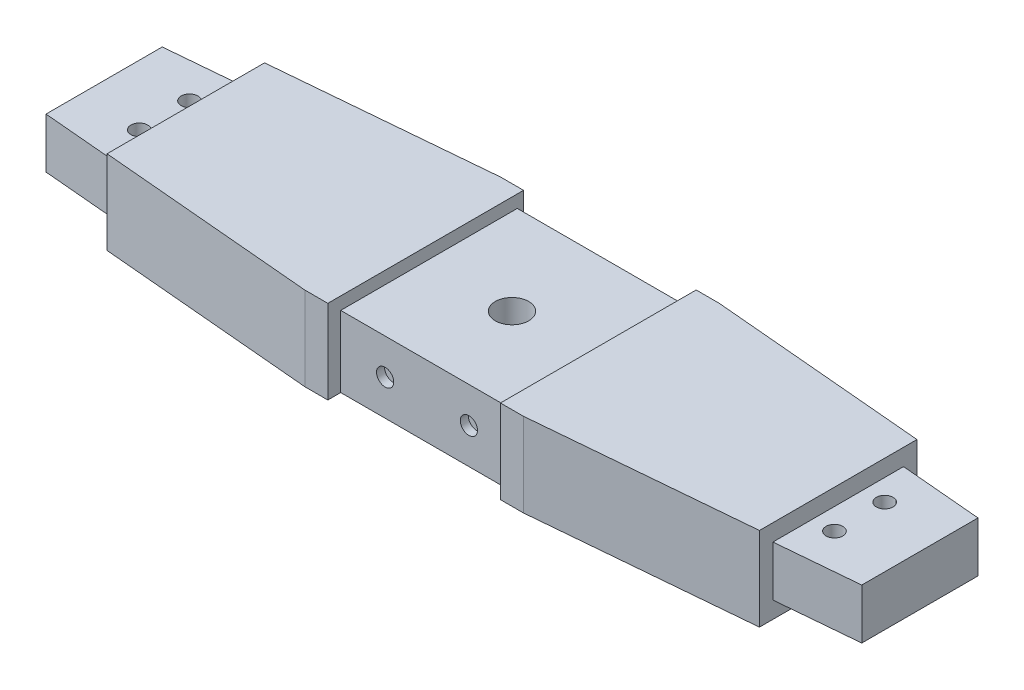
SolidWorks part; units mm, degrees
ref_plane "Front Plane" through (0, 0, 0) normal (0, 0, 1) x (1, 0, 0)
ref_plane "Top Plane" through (0, 0, 0) normal (0, 1, 0) x (1, 0, 0)
ref_plane "Right Plane" through (0, 0, 0) normal (1, 0, 0) x (0, 0, -1)
ref_plane "Plane1" through (0, 13, 0) normal (0, 1, 0) x (1, 0, 0)
sketch "Sketch1" plane through (0, 13, 0) normal (0, 1, 0) x (1, 0, 0)
  line L0 (-26.0808, -23.37) -> (26.0808, -23.37)
  line L1 (26.0808, -23.37) -> (77.9, -18.8062)
  line L2 (77.9, -18.8062) -> (77.9, 18.8062)
  line L3 (77.9, 18.8062) -> (26.0808, 23.37)
  line L4 (26.0808, 23.37) -> (-26.0808, 23.37)
  line L5 (-26.0808, 23.37) -> (-77.9, 18.8062)
  line L6 (-77.9, 18.8062) -> (-77.9, -18.8062)
  line L7 (-77.9, -18.8062) -> (-26.0808, -23.37)
  dimension "D1" = 155.8
extrude "Boss-Extrude1" add sketch "Sketch1" against normal blind 17
sketch "Sketch2" plane through (0, -4, 0) normal (0, -1, 0) x (1, 0, 0)
  line L0 (20.6099, 23.37) -> (-20.6099, 23.37)
  line L1 (-20.6099, 23.37) -> (-20.6099, 20.2958)
  line L2 (-20.6099, 20.2958) -> (20.6099, 20.2958)
  line L3 (20.6099, 20.2958) -> (20.6099, 23.37)
extrude "Cut-Extrude1" cut sketch "Sketch2" against normal through all
sketch "Sketch3" plane through (0, -4, 0) normal (0, -1, 0) x (1, 0, 0)
  line L0 (-20.6099, -23.37) -> (20.6099, -23.37)
  line L1 (20.6099, -23.37) -> (20.6099, -21.87)
  line L2 (20.6099, -21.87) -> (-20.6099, -21.87)
  line L3 (-20.6099, -21.87) -> (-20.6099, -23.37)
extrude "Cut-Extrude2" cut sketch "Sketch3" against normal through all
sketch "Sketch4" plane through (0, 13, 0) normal (0, 1, 0) x (-1, 0, 0)
  line L0 (-20.6099, 20.2958) -> (-20.6099, 23.37) construction
  line L1 (-20.6099, 23.37) -> (-26.0808, 23.37) construction
  line L2 (-20.6099, -23.37) -> (-20.6099, -21.87) construction
  line L3 (-26.0808, -23.37) -> (-20.6099, -23.37) construction
  line L4 (-77.9, -18.8062) -> (-26.0808, -23.37) construction
  line L5 (-77.9, 18.8062) -> (-77.9, -18.8062) construction
  line L6 (-26.0808, 23.37) -> (-77.9, 18.8062) construction
  line L7 (-20.6099, 20.2958) -> (-20.6099, 23.37)
  line L8 (-20.6099, 23.37) -> (-26.0808, 23.37)
  line L9 (-20.6099, -23.37) -> (-20.6099, -21.87)
  line L10 (-26.0808, -23.37) -> (-20.6099, -23.37)
  line L11 (-77.9, -18.8062) -> (-26.0808, -23.37)
  line L12 (-77.9, 18.8062) -> (-77.9, -18.8062)
  line L13 (-26.0808, 23.37) -> (-77.9, 18.8062)
  line L14 (-20.6099, 20.2958) -> (-20.6099, -21.87)
extrude "Boss-Extrude2" add sketch "Sketch4" along normal blind 3
sketch "Sketch5" plane through (0, 13, 0) normal (0, 1, 0) x (-1, 0, 0)
  line L0 (20.6099, -21.87) -> (20.6099, -23.37) construction
  line L1 (20.6099, -23.37) -> (26.0808, -23.37) construction
  line L2 (26.0808, -23.37) -> (77.9, -18.8062) construction
  line L3 (77.9, -18.8062) -> (77.9, 18.8062) construction
  line L4 (77.9, 18.8062) -> (26.0808, 23.37) construction
  line L5 (20.6099, 23.37) -> (20.6099, 20.2958) construction
  line L6 (26.0808, 23.37) -> (20.6099, 23.37) construction
  line L7 (20.6099, -21.87) -> (20.6099, -23.37)
  line L8 (20.6099, -23.37) -> (26.0808, -23.37)
  line L9 (26.0808, -23.37) -> (77.9, -18.8062)
  line L10 (77.9, -18.8062) -> (77.9, 18.8062)
  line L11 (77.9, 18.8062) -> (26.0808, 23.37)
  line L12 (20.6099, 23.37) -> (20.6099, 20.2958)
  line L13 (26.0808, 23.37) -> (20.6099, 23.37)
  line L14 (20.6099, 20.2958) -> (20.6099, -21.87)
extrude "Boss-Extrude3" add sketch "Sketch5" along normal blind 3
sketch "Sketch6" plane through (77.9, 0, 0) normal (1, 0, 0) x (0, 0, -1)
  line L0 (15.5964, 0) -> (-15.5964, 0)
  line L1 (-15.5964, 0) -> (-15.5964, 12)
  line L2 (-15.5964, 12) -> (15.5964, 12)
  line L3 (15.5964, 12) -> (15.5964, 0)
extrude "Boss-Extrude4" add sketch "Sketch6" along normal blind 19.5
sketch "Sketch7" plane through (-77.9, 0, 0) normal (-1, 0, 0) x (0, 0, 1)
  line L0 (15.5964, 0) -> (-15.5964, 0)
  line L1 (-15.5964, 0) -> (-15.5964, 12)
  line L2 (-15.5964, 12) -> (15.5964, 12)
  line L3 (15.5964, 12) -> (15.5964, 0)
extrude "Boss-Extrude5" add sketch "Sketch7" along normal blind 19.5
draft "Draft1" type of draft neutral plane draft angle 5.033 faces to draft 2 face at (-87.65, 6, 15.5964) face at (-87.65, 6, -15.5964) neutral plane through (-77.9, -4, -18.8062) neutral plane normal (-1, 0, 0) parameters "D1"=5.033
draft "Draft2" type of draft neutral plane draft angle 5.033 faces to draft 2 face at (87.65, 6, 15.5964) face at (87.65, 6, -15.5964) neutral plane through (77.9, -4, 18.8062) neutral plane normal (1, 0, 0) parameters "D1"=5.033
hole_wizard "Ø4.1 (4.1) Diameter Hole1" positions "Sketch9" profile "Sketch8" hole size "Ø4.1" standard "ANSI Metric"
sketch "Sketch9" plane through (0, 0, 23.37) normal (0, 0, 1) x (1, 0, 0)
  point P0 (-10, 4.5)
  point P1 (10, 4.5)
sketch "Sketch8" plane through (-10, 4.5, 23.37) normal (1, 0, 0) x (0, -1, 0)
  line L0 (0, 0) -> (0, 5)
  line L1 (0, 5) -> (2.05, 5)
  line L2 (2.05, 5) -> (2.05, 0)
  line L5 (2.05, 0) -> (0, 0)
  line L10 (0, 5) -> (-2.05, 5) construction
  line L11 (0, -6.35) -> (0, 107.95) construction
  dimension "Hole Dia." = 4.1
  dimension "Hole Depth" = 5
  dimension "Drill Angle" = 180
hole_wizard "Ø4.0 (4) Diameter Hole1" positions "Sketch11" profile "Sketch10" hole size "Ø4.0" standard "ANSI Metric"
sketch "Sketch11" plane through (0, 12, 0) normal (0, 1, 0) x (1, 0, 0)
  point P0 (-83, 6)
  point P1 (-83, -6)
  point P2 (83, -6)
  point P3 (83, 6)
sketch "Sketch10" plane through (-83, 12, -6) normal (1, 0, 0) x (0, 0, 1)
  line L0 (0, 0) -> (0, 16)
  line L1 (0, 16) -> (2, 16)
  line L2 (2, 16) -> (2, 0)
  line L5 (2, 0) -> (0, 0)
  line L11 (0, -6.35) -> (0, 107.95) construction
  dimension "Thru Hole Dia." = 4
  dimension "Thru Hole Depth" = 16
hole_wizard "Ø8.0 (8) Diameter Hole1" positions "Sketch13" profile "Sketch12" hole size "Ø8.0" standard "ANSI Metric"
sketch "Sketch13" plane through (0, -4, 0) normal (0, -1, 0) x (-1, 0, 0)
  point P0 (0, 0)
sketch "Sketch12" plane through (0, -4, 0) normal (1, 0, 0) x (0, 0, -1)
  line L0 (0, 0) -> (0, 20)
  line L1 (0, 20) -> (4, 20)
  line L2 (4, 20) -> (4, 0)
  line L5 (4, 0) -> (0, 0)
  line L11 (0, -6.35) -> (0, 107.95) construction
  dimension "Thru Hole Dia." = 8
  dimension "Thru Hole Depth" = 20
